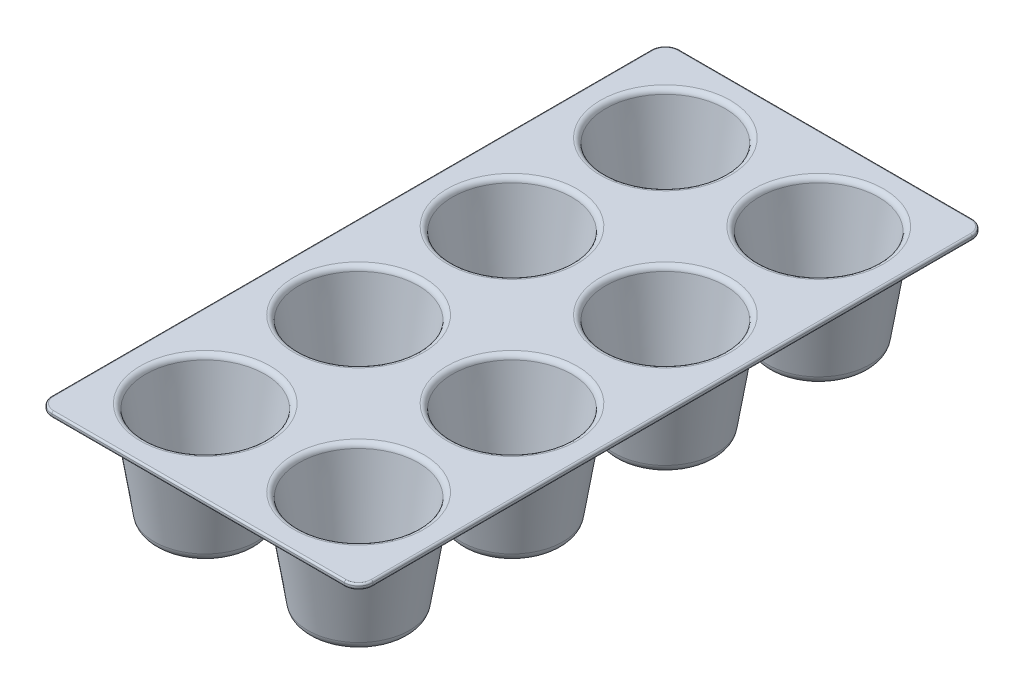
SolidWorks part; units mm, degrees
material "PE High Density"
ref_plane "Front Plane" through (0, 0, 0) normal (0, 0, 1) x (1, 0, 0)
ref_plane "Top Plane" through (0, 0, 0) normal (0, 1, 0) x (1, 0, 0)
ref_plane "Right Plane" through (0, 0, 0) normal (1, 0, 0) x (0, 0, -1)
sketch "Sketch1" plane through (0, 0, 0) normal (0, 0, 1) x (1, 0, 0)
  line L0 (0, 0) -> (0, 60.9163) construction
  line L1 (0, 0) -> (-22.6021, 0)
  line L2 (-28.5283, 5.0614) -> (-36.0369, 52.4693)
  line L3 (-39, 55) -> (-47, 55)
  line L4 (-47, 55) -> (-47, 58)
  line L5 (-47, 58) -> (-36.4378, 58)
  line L6 (-33.4747, 55.4693) -> (-25.966, 8.0614)
  line L7 (-20.0399, 3) -> (0, 3)
  line L8 (0, 3) -> (0, 0)
  arc A0 (-25.966, 8.0614) -> (-20.0399, 3) centre (-20.0399, 9) ccw
  arc A1 (-22.6021, 0) -> (-28.5283, 5.0614) centre (-22.6021, 6) cw
  arc A2 (-36.4378, 58) -> (-33.4747, 55.4693) centre (-36.4378, 55) cw
  arc A3 (-36.0369, 52.4693) -> (-39, 55) centre (-39, 52) ccw
  point P3 (-58.35, 55)
  point P19 (-53.4964, 55)
  dimension "D4" = 6
  dimension "D6" = 3
  dimension "D1" = 58
  dimension "D2" = 3
  dimension "D3" = 3
  dimension "D5" = 9
  dimension "D7" = 78
  dimension "D8" = 8
revolve "Revolve1" add sketch "Sketch1" angle 360 about L0
pattern_linear "LPattern1" count 2 spacing 86 along (1, 0, 0) count 4 spacing 86 along (0, 0, -1) of "Revolve1"
sketch "Sketch3" plane through (0, 0, 0) normal (0, 1, 0) x (1, 0, 0)
  line L1 (-39, -47) -> (125, -47)
  line L2 (-47, -39) -> (-47, 297)
  line L3 (-39, 305) -> (125, 305)
  line L4 (133, -39) -> (133, 297)
  line L5 (-47, -47) -> (133, 305) construction
  line L6 (-47, 305) -> (133, -47) construction
  arc A0 (43, 276.9737) -> (-18.9737, 215) centre (0, 258) ccw construction
  arc A1 (-18.9737, 215) -> (-18.9737, 129) centre (0, 172) ccw construction
  arc A2 (104.9737, 129) -> (104.9737, 215) centre (86, 172) ccw construction
  arc A3 (43, -18.9737) -> (104.9737, 43) centre (86, 0) ccw construction
  arc A4 (-18.9737, 129) -> (-18.9737, 43) centre (0, 86) ccw construction
  arc A5 (-18.9737, 43) -> (43, -18.9737) centre (0, 0) ccw construction
  arc A6 (43, 18.9737) -> (18.9737, 43) centre (0, 0) ccw construction
  arc A7 (18.9737, 43) -> (43, 67.0263) centre (0, 86) ccw construction
  arc A8 (43, 67.0263) -> (67.0263, 43) centre (86, 86) ccw construction
  arc A9 (67.0263, 43) -> (43, 18.9737) centre (86, 0) ccw construction
  arc A10 (104.9737, 43) -> (104.9737, 129) centre (86, 86) ccw construction
  arc A11 (67.0263, 129) -> (43, 104.9737) centre (86, 86) ccw construction
  arc A12 (43, 153.0263) -> (67.0263, 129) centre (86, 172) ccw construction
  arc A13 (43, 104.9737) -> (18.9737, 129) centre (0, 86) ccw construction
  arc A14 (18.9737, 129) -> (43, 153.0263) centre (0, 172) ccw construction
  arc A15 (104.9737, 215) -> (43, 276.9737) centre (86, 258) ccw construction
  arc A16 (67.0263, 215) -> (43, 190.9737) centre (86, 172) ccw construction
  arc A17 (43, 239.0263) -> (67.0263, 215) centre (86, 258) ccw construction
  arc A18 (18.9737, 215) -> (43, 239.0263) centre (0, 258) ccw construction
  arc A19 (43, 190.9737) -> (18.9737, 215) centre (0, 172) ccw construction
  arc A20 (-18.9737, 129) -> (-18.9737, 43) centre (0, 86) ccw
  arc A21 (-18.9737, 43) -> (43, -18.9737) centre (0, 0) ccw
  arc A22 (43, 18.9737) -> (18.9737, 43) centre (0, 0) ccw
  arc A23 (18.9737, 43) -> (43, 67.0263) centre (0, 86) ccw
  arc A24 (43, 67.0263) -> (67.0263, 43) centre (86, 86) ccw
  arc A25 (67.0263, 43) -> (43, 18.9737) centre (86, 0) ccw
  arc A26 (43, -18.9737) -> (104.9737, 43) centre (86, 0) ccw
  arc A27 (104.9737, 43) -> (104.9737, 129) centre (86, 86) ccw
  arc A28 (67.0263, 129) -> (43, 104.9737) centre (86, 86) ccw
  arc A29 (43, 153.0263) -> (67.0263, 129) centre (86, 172) ccw
  arc A30 (43, 104.9737) -> (18.9737, 129) centre (0, 86) ccw
  arc A31 (18.9737, 129) -> (43, 153.0263) centre (0, 172) ccw
  arc A32 (-18.9737, 215) -> (-18.9737, 129) centre (0, 172) ccw
  arc A33 (43, 276.9737) -> (-18.9737, 215) centre (0, 258) ccw
  arc A34 (104.9737, 215) -> (43, 276.9737) centre (86, 258) ccw
  arc A35 (104.9737, 129) -> (104.9737, 215) centre (86, 172) ccw
  arc A36 (67.0263, 215) -> (43, 190.9737) centre (86, 172) ccw
  arc A37 (43, 239.0263) -> (67.0263, 215) centre (86, 258) ccw
  arc A38 (18.9737, 215) -> (43, 239.0263) centre (0, 258) ccw
  arc A39 (43, 190.9737) -> (18.9737, 215) centre (0, 172) ccw
  arc A40 (-39, -47) -> (-47, -39) centre (-39, -39) cw
  arc A41 (125, -47) -> (133, -39) centre (125, -39) ccw
  arc A42 (125, 305) -> (133, 297) centre (125, 297) cw
  arc A43 (-47, 297) -> (-39, 305) centre (-39, 297) cw
  point P0 (43, 129)
  dimension "D1" = 8
extrude "Boss-Extrude1" add sketch "Sketch3" against normal blind 3 from surface at 58 contours A40 L1 A21 L2 | A26 A21 L1 | L1 A41 L4 A26 | A27 A26 L4 | A35 A27 L4 | A25 A24 A23 A22 | A31 A30 A28 A29 | A32 L2 A20 | A21 A20 L2 | A35 L4 A34 | A39 A36 A37 A38 | A33 L2 A32 | A43 L2 A33 L3 | A34 L3 A33 | A42 L3 A34 L4 starting at face at (43, 58, -215)
fillet "Fillet1" radius 1 16 edges at (43, 58, 47) (43, 55, 47) (130.6569, 58, 44.6569) (130.6569, 55, 44.6569) (133, 58, -129) (133, 55, -129) (130.6569, 58, -302.6569) (130.6569, 55, -302.6569) (43, 58, -305) (43, 55, -305) (-44.6569, 58, -302.6569) (-44.6569, 55, -302.6569) (-47, 58, -129) (-47, 55, -129) (-44.6569, 58, 44.6569) (-44.6569, 55, 44.6569)
equation "\"A\"= 3"
equation "\"B\"= 78"
equation "\"C\"= 8"
equation "\"D2@Sketch1\"=\"A\""
equation "\"D3@Sketch1\"=\"D2@Sketch1\""
equation "\"D7@Sketch1\"=\"B\""
equation "\"D8@Sketch1\"=\"C\""
equation "\"D4@LPattern1\"=\"B\"+\"C\""
equation "\"D3@LPattern1\"=\"B\"+\"C\""
equation "\"D1@Sketch3\"=\"C\""
